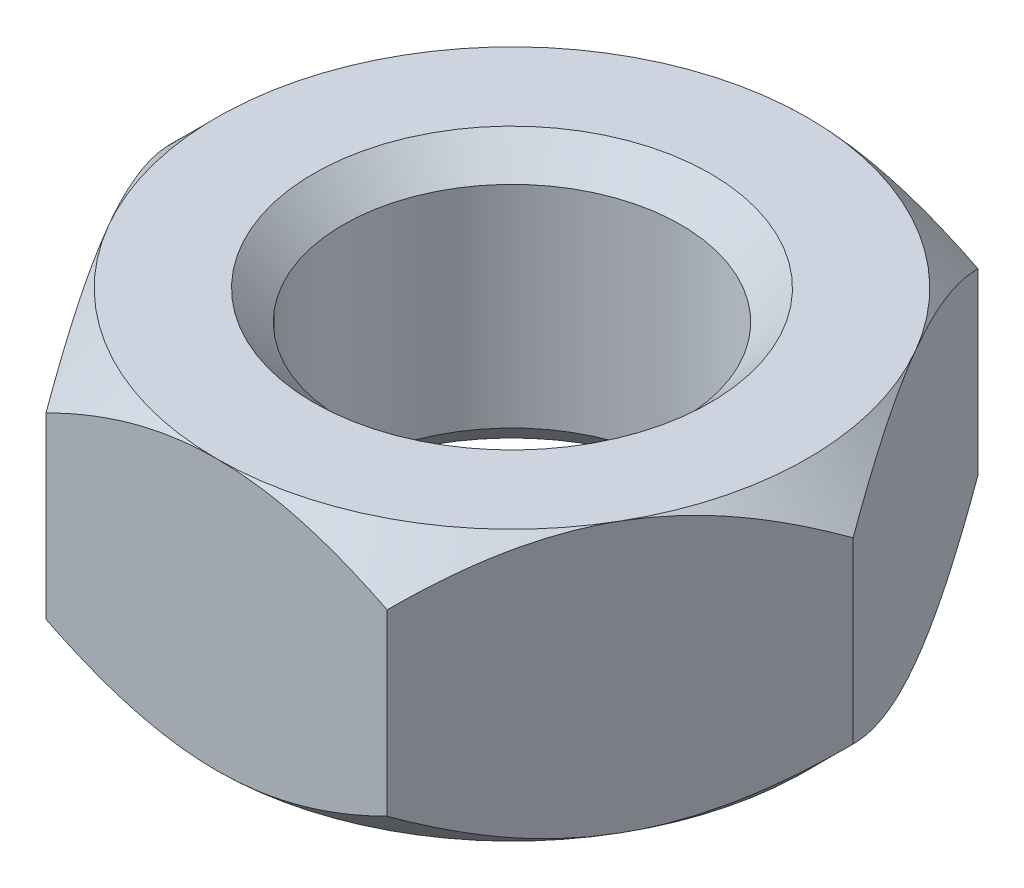
SolidWorks part; units mm, degrees
material "Cast Stainless Steel"
ref_plane "Front Plane" through (0, 0, 0) normal (0, 0, 1) x (1, 0, 0)
ref_plane "Top Plane" through (0, 0, 0) normal (0, 1, 0) x (1, 0, 0)
ref_plane "Right Plane" through (0, 0, 0) normal (1, 0, 0) x (0, 0, -1)
sketch "Sketch1" plane through (0, 0, 0) normal (0, 1, 0) x (1, 0, 0)
  line L0 (-4.0415, 0) -> (4.0415, 0) construction
  line L1 (4.0415, 0) -> (2.0207, 3.5)
  line L2 (2.0207, 3.5) -> (-2.0207, 3.5)
  line L3 (-2.0207, 3.5) -> (-4.0415, 0)
  line L4 (-4.0415, 0) -> (-2.0207, -3.5)
  line L5 (-2.0207, -3.5) -> (2.0207, -3.5)
  line L6 (2.0207, -3.5) -> (4.0415, 0)
  circle A0 centre (0, 0) radius 3.5 construction
  circle A1 centre (0, 0) radius 2
  point P12 (0, 0)
  dimension "D1" = 4
  dimension "D2" = 7
extrude "Boss-Extrude1" add sketch "Sketch1" along normal blind 3.2
sketch "Sketch3" plane through (0, 0, 0) normal (1, 0, 0) x (0, 0, -1)
  line L0 (-3.5, 0) -> (-4.0415, 0.5415)
  line L1 (-4.0415, 0.5415) -> (-4.0415, 0)
  line L2 (-4.0415, 0) -> (-3.5, 0)
  line L4 (-3.5, 1.6) -> (3.5, 1.6) construction
  line L6 (3.5, 3.2) -> (3.5, 0) construction
  line L7 (-4.0415, 3.2) -> (-3.5, 3.2)
  line L8 (-4.0415, 2.6585) -> (-4.0415, 3.2)
  line L9 (-3.5, 3.2) -> (-4.0415, 2.6585)
  line L10 (0, 0) -> (0, 3.2) construction
  line L12 (-3.5, 3.2) -> (-3.5, 0) construction
  point P7 (0, 1.6)
  dimension "D1" = 1.6
  dimension "D2" = 45
  dimension "D3" = 4.0415
revolve "Cut-Revolve1" cut sketch "Sketch3" angle 360 about L10
chamfer "Chamfer1" distance 0.35 angle 45 2 edges at (0, 0, 2) (0, 3.2, 2)
equation "\"d\"= 4"
equation "\"m\"= 3.2"
equation "\"s\"= 7"
equation "\"e\"= 7.66"
equation "\"D1@Sketch1\"=\"d\""
equation "\"D2@Sketch1\"=\"s\""
equation "\"D1@Boss-Extrude1\"=\"m\""
equation "\"D1@Sketch3\"=\"m\"/2"
equation "\"D3@Sketch3\"= \"s\" / sqr(3)"
equation "\"D1@Chamfer1\"=\"s\"/20"
